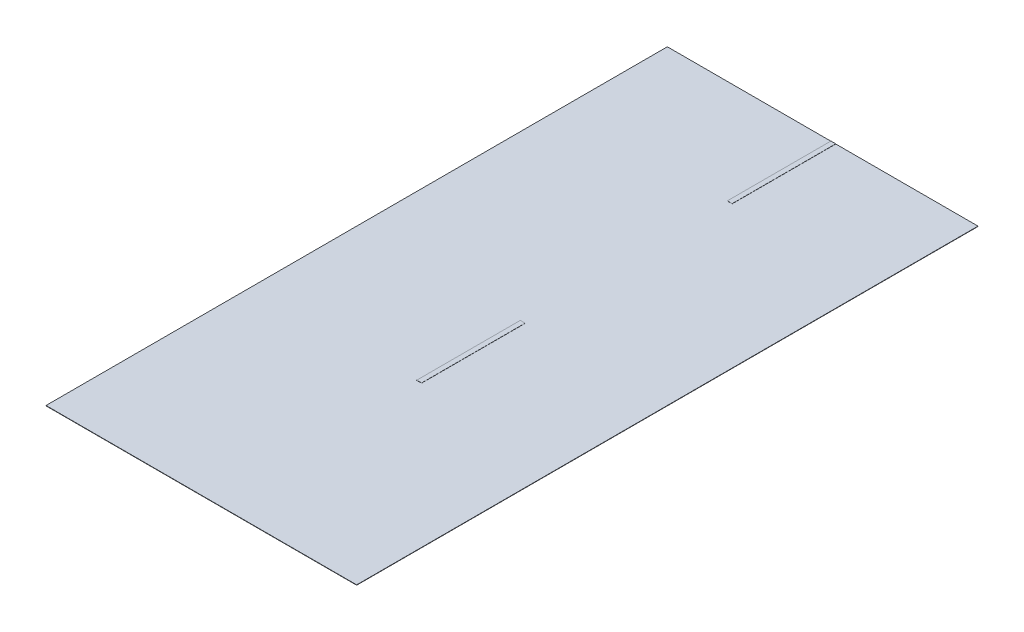
SolidWorks part; units mm, degrees
ref_plane "Front Plane" through (0, 0, 0) normal (0, 0, 1) x (1, 0, 0)
ref_plane "Top Plane" through (0, 0, 0) normal (0, 1, 0) x (1, 0, 0)
ref_plane "Right Plane" through (0, 0, 0) normal (1, 0, 0) x (0, 0, -1)
sketch "Sketch3" plane through (0, 0, 0) normal (0, 1, 0) x (1, 0, 0)
  line L0 (-4572, 0) -> (4572, 0)
  line L1 (4572, 0) -> (4572, -18288)
  line L2 (-4572, 0) -> (-4572, -18288)
  line L3 (-4572, -18288) -> (4572, -18288)
  line L4 (0, 0) -> (0, -18288) construction
  point P4 (0, 0)
  dimension "D1" = 9144
  dimension "D2" = 18288
  dimension "D3" = 18288
extrude "Boss-Extrude1" add sketch "Sketch3" along normal blind 10
sketch "Sketch4" plane through (0, 10, 0) normal (0, 1, 0) x (1, 0, 0)
  line L0 (4572, 0) -> (-4572, 0) construction
  line L1 (233.6356, 0) -> (386.0356, 0)
  line L2 (233.6356, 0) -> (233.6356, -3048)
  line L3 (233.6356, -3048) -> (386.0356, -3048)
  line L4 (386.0356, 0) -> (386.0356, -3048)
  line L5 (233.6356, 0) -> (386.0356, -3048) construction
  line L6 (233.6356, -3048) -> (386.0356, 0) construction
  line L7 (396.0356, 0) -> (396.0356, -3048)
  line L8 (243.6356, 0) -> (243.6356, -3048)
  line L9 (243.6356, 0) -> (396.0356, 0)
  line L10 (243.6356, -3048) -> (396.0356, -3048)
  line L11 (396.0356, -9144) -> (396.0356, -12192)
  line L12 (243.6356, -9144) -> (243.6356, -12192)
  line L13 (243.6356, -9144) -> (396.0356, -9144)
  line L14 (243.6356, -12192) -> (396.0356, -12192)
  line L15 (386.0356, -9144) -> (386.0356, -12192)
  line L16 (233.6356, -9144) -> (233.6356, -12192)
  line L17 (233.6356, -9144) -> (386.0356, -9144)
  line L18 (233.6356, -12192) -> (386.0356, -12192)
  point P0 (309.8356, -1524)
  line M5 (4572, 0) -> (-4572, 0)
  dimension "D1" = 3048
  dimension "D2" = 152.4
  dimension "D3" = 0
  dimension "D4" = 2
  dimension "D5" = 2
extrude "Boss-Extrude2" add sketch "Sketch4" along normal blind 5 contours L15 L13 L12 L14 | L8 L3 L4 M5
